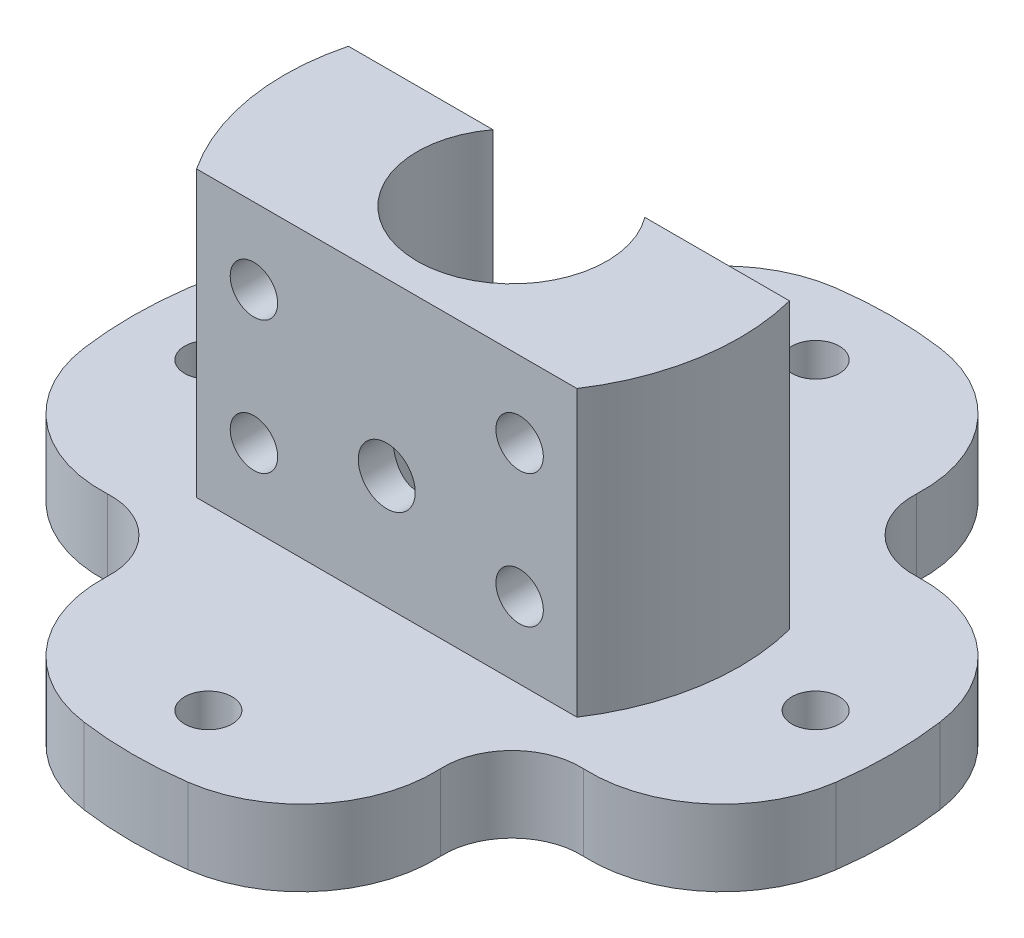
SolidWorks part; units mm, degrees
material "6061 合金"
ref_plane "前视基准面" through (0, 0, 0) normal (0, 0, 1) x (1, 0, 0)
ref_plane "上视基准面" through (0, 0, 0) normal (0, 1, 0) x (1, 0, 0)
ref_plane "右视基准面" through (0, 0, 0) normal (1, 0, 0) x (0, 0, -1)
other "Configuration Table"
sketch "草图1" plane through (0, 0, 0) normal (0, 1, 0) x (1, 0, 0)
  line L0 (-11.619, 3) -> (11.619, 3)
  line L1 (-10.022, -6.6) -> (10.022, -6.6)
  line L2 (0, 25.9007) -> (0, -26.4323) construction
  line L3 (0, 0) -> (16, 0) construction
  line L4 (-12.3744, 12.3744) -> (0, 0) construction
  circle A0 centre (0, 0) radius 5
  circle A1 centre (0, 0) radius 12
  circle A2 centre (0, 0) radius 20
  circle A3 centre (0, 0) radius 16 construction
  circle A4 centre (16, 0) radius 1.25
  circle A5 centre (0, -16) radius 1.25
  circle A6 centre (-16, 0) radius 1.25
  circle A7 centre (0, 16) radius 1.25
  circle A8 centre (0, 16) radius 3 construction
  circle A9 centre (0, 0) radius 17.5 construction
  circle A10 centre (-12.3744, 12.3744) radius 3.6
  circle A11 centre (12.3744, 12.3744) radius 3.6
  circle A12 centre (12.3744, -12.3744) radius 3.6
  circle A13 centre (-12.3744, -12.3744) radius 3.6
  circle A14 centre (16, 0) radius 3 construction
  circle A15 centre (0, -16) radius 3 construction
  circle A16 centre (-16, 0) radius 3 construction
  point P23 (0, 0)
  point P34 (0, 0)
  point P41 (0, 0)
  dimension "D1" = 10
  dimension "D2" = 24
  dimension "D3" = 40
  dimension "D4" = 32
  dimension "D7" = 2.5
  dimension "D9" = 6
  dimension "D11" = 35
  dimension "D12" = 7.2
  dimension "D5" = 3
  dimension "D6" = 6.6
  dimension "D8" = 90
  dimension "D10" = 4
  dimension "D15" = 45
  dimension "D14" = 4
  dimension "D13" = 4
sketch "草图2" plane through (0, 0, 0) normal (0, 1, 0) x (1, 0, 0)
  line L0 (-10.022, -6.6) -> (10.022, -6.6) construction
  line L1 (-10.022, -6.6) -> (10.022, -6.6)
  line L2 (-11.619, 3) -> (11.619, 3) construction
  line L3 (-11.619, 3) -> (-4, 3)
  line L4 (4, 3) -> (11.619, 3)
  circle A0 centre (0, 0) radius 5 construction
  circle A1 centre (0, 0) radius 12 construction
  arc A2 (-4, 3) -> (4, 3) centre (0, 0) ccw
  arc A3 (-11.619, 3) -> (-10.022, -6.6) centre (0, 0) ccw
  arc A4 (10.022, -6.6) -> (11.619, 3) centre (0, 0) ccw
extrude "凸台-拉伸1" add sketch "草图2" along normal blind 15
sketch "草图3" plane through (0, 0, 0) normal (0, 1, 0) x (1, 0, 0)
  circle A0 centre (0, -16) radius 1.25 construction
  circle A1 centre (16, 0) radius 1.25 construction
  circle A2 centre (-16, 0) radius 1.25 construction
  circle A3 centre (0, 16) radius 1.25 construction
  circle A4 centre (0, 0) radius 5 construction
  circle A5 centre (0, 0) radius 20 construction
  circle A6 centre (0, -16) radius 1.25
  circle A7 centre (16, 0) radius 1.25
  circle A8 centre (-16, 0) radius 1.25
  circle A9 centre (0, 16) radius 1.25
  circle A10 centre (0, 0) radius 5
  circle A11 centre (0, 0) radius 20
extrude "凸台-拉伸2" add sketch "草图3" against normal blind 4
cosmetic thread "装饰螺纹线1" parameters "D2"=3
cosmetic thread "装饰螺纹线2" parameters "D2"=3
cosmetic thread "装饰螺纹线3" parameters "D2"=3
cosmetic thread "装饰螺纹线4" parameters "D2"=3
sketch "草图4" plane through (0, 0, 0) normal (0, 1, 0) x (1, 0, 0)
  circle A0 centre (12.3744, -12.3744) radius 3.6 construction
  circle A1 centre (12.3744, 12.3744) radius 3.6 construction
  circle A2 centre (-12.3744, 12.3744) radius 3.6 construction
  circle A3 centre (-12.3744, -12.3744) radius 3.6 construction
  circle A4 centre (12.3744, -12.3744) radius 3.6
  circle A5 centre (12.3744, 12.3744) radius 3.6
  circle A6 centre (-12.3744, 12.3744) radius 3.6
  circle A7 centre (-12.3744, -12.3744) radius 3.6
extrude "切除-拉伸1" cut sketch "草图4" against normal through all
fillet "圆角1" radius 7 8 edges at (15.96, -2, 12.0531) (12.0531, -2, 15.96) (-12.0531, -2, 15.96) (-15.96, -2, 12.0531) (-15.96, -2, -12.0531) (-12.0531, -2, -15.96) (12.0531, -2, -15.96) (15.96, -2, -12.0531)
sketch "草图5" plane through (0, 0, -3) normal (0, 0, -1) x (-1, 0, 0)
  line L0 (-11.619, 15) -> (-4, 15) construction
  line L1 (7, 11) -> (-7, 11) construction
  line L2 (7, 11) -> (7, 4) construction
  line L3 (7, 4) -> (-7, 4) construction
  line L4 (-7, 11) -> (-7, 4) construction
  line L5 (7, 11) -> (-7, 4) construction
  line L6 (7, 4) -> (-7, 11) construction
  circle A0 centre (-7, 11) radius 1.25
  circle A1 centre (-7, 4) radius 1.25
  circle A2 centre (7, 11) radius 1.25
  circle A3 centre (7, 4) radius 1.25
  circle A4 centre (0, 6) radius 1.5
  point P0 (0, 7.5)
  dimension "D4" = 2.5
  dimension "D5" = 3
  dimension "D6" = 2
  dimension "D1" = 4
  dimension "D2" = 7
  dimension "D3" = 14
extrude "切除-拉伸2" cut sketch "草图5" against normal through all
cosmetic thread "装饰螺纹线5" parameters "D2"=3
cosmetic thread "装饰螺纹线6" parameters "D2"=3
cosmetic thread "装饰螺纹线7" parameters "D2"=3
cosmetic thread "装饰螺纹线8" parameters "D2"=3
chamfer "倒角1" [suppressed] distance 1 angle 45
sketch "草图6" [suppressed] plane through (0, -4, 0) normal (0, -1, 0) x (1, 0, 0)
  line L1 (-25, -25) -> (25, -25)
  line L2 (-25, -25) -> (-25, 25)
  line L3 (-25, 25) -> (25, 25)
  line L4 (25, -25) -> (25, 25)
  line L5 (-25, -25) -> (25, 25) construction
  line L6 (-25, 25) -> (25, -25) construction
  point P0 (0, 0)
  dimension "D1" = 50
  dimension "D2" = 50
